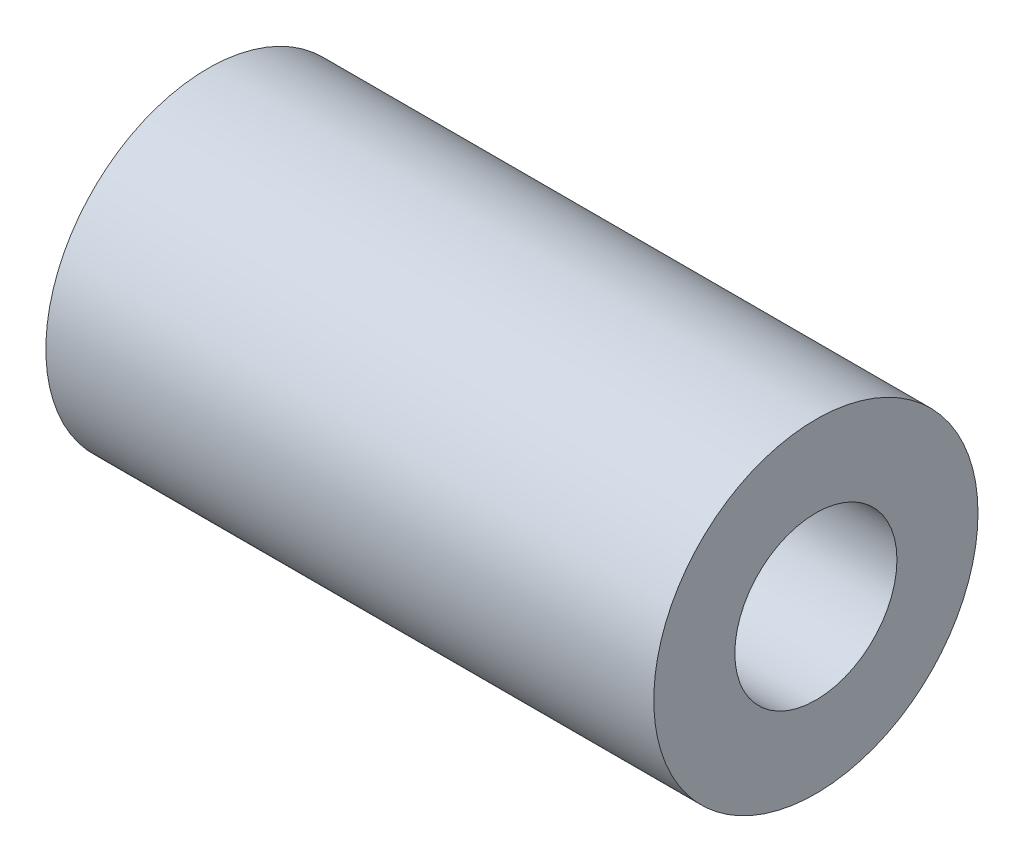
SolidWorks part; units mm, degrees
ref_plane "Front Plane" through (0, 0, 0) normal (1, 0, 0) x (0, 1, 0)
ref_plane "Top Plane" through (0, 0, 0) normal (0, 0, 1) x (0, 1, 0)
ref_plane "Right Plane" through (0, 0, 0) normal (0, 1, 0) x (-1, 0, 0)
sketch "Sketch1" plane through (0, 0, 0) normal (1, 0, 0) x (0, 1, 0)
  circle A0 centre (0, 0) radius 4
  circle A1 centre (0, 0) radius 2
  dimension "D1" = 4
  dimension "D2" = 8
extrude "Boss-Extrude1" add sketch "Sketch1" along normal blind 15
